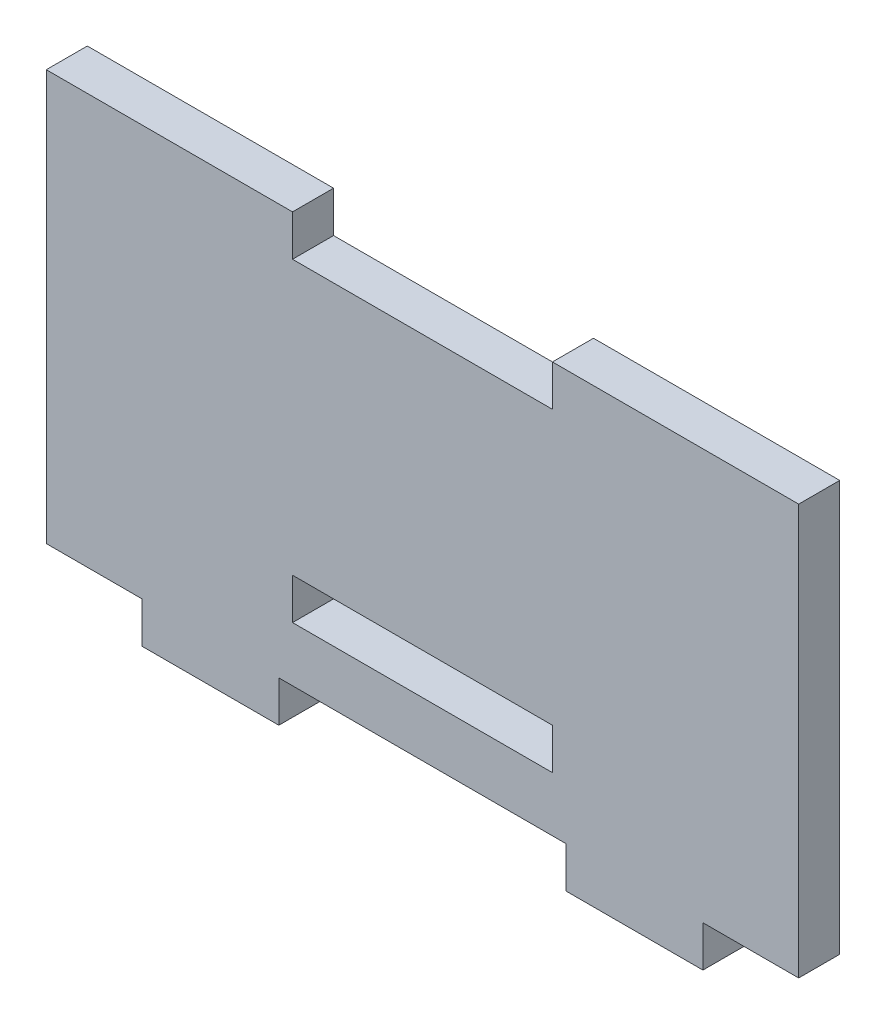
SolidWorks part; units mm, degrees
ref_plane "Front Plane" through (0, 0, 0) normal (0, 0, 1) x (1, 0, 0)
ref_plane "Top Plane" through (0, 0, 0) normal (0, 1, 0) x (1, 0, 0)
ref_plane "Right Plane" through (0, 0, 0) normal (1, 0, 0) x (0, 0, -1)
sketch "Sketch1" plane through (0, 0, 0) normal (0, 0, 1) x (1, 0, 0)
  line L0 (0, 0) -> (0, 30)
  line L1 (0, 30) -> (18, 30)
  line L2 (18, 30) -> (18, 27)
  line L3 (18, 27) -> (37, 27)
  line L4 (37, 27) -> (37, 30)
  line L5 (37, 30) -> (55, 30)
  line L6 (55, 30) -> (55, 0)
  line L7 (0, 0) -> (7, 0)
  line L8 (27.5, 27) -> (27.5, 7) construction
  line L9 (38, 0) -> (31, 0)
  line L11 (7, 0) -> (7, -3)
  line L12 (7, -3) -> (17, -3)
  line L13 (17, -3) -> (17, 0)
  line L14 (17, 0) -> (24, 0)
  line L15 (38, -3) -> (38, 0)
  line L16 (48, -3) -> (38, -3)
  line L17 (48, 0) -> (48, -3)
  line L19 (55, 0) -> (48, 0)
  line L21 (37, 7) -> (37, 4)
  line L22 (37, 7) -> (18, 7)
  line L23 (27.5, 7) -> (27.5, 4)
  line L24 (37, 4) -> (18, 4)
  line L25 (18, 7) -> (18, 4)
  line L26 (24, 0) -> (31, 0)
  dimension "D1" = 30
  dimension "D2" = 18
  dimension "D3" = 19
  dimension "D4" = 18
  dimension "D6" = 3
  dimension "D7" = 3
  dimension "D8" = 7
  dimension "D9" = 10
  dimension "D10" = 7
  dimension "D11" = 3
  dimension "D12" = 30
  dimension "D13" = 3
  dimension "D14" = 20
  dimension "D15" = 9.5
  dimension "D16" = 3
extrude "Boss-Extrude1" add sketch "Sketch1" along normal blind 3
